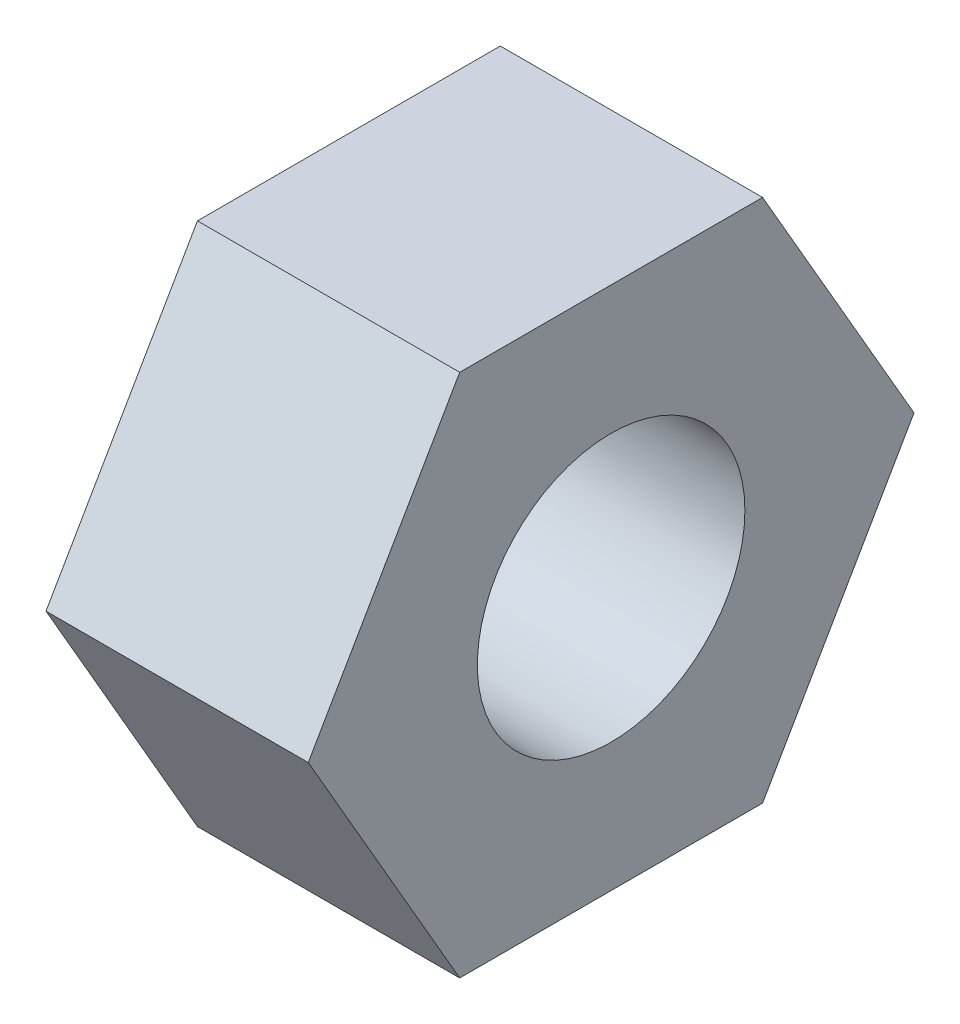
SolidWorks part; units mm, degrees
ref_plane "前视基准面" through (0, 0, 0) normal (0, 0, 1) x (1, 0, 0)
ref_plane "上视基准面" through (0, 0, 0) normal (0, 1, 0) x (1, 0, 0)
ref_plane "右视基准面" through (0, 0, 0) normal (1, 0, 0) x (0, 0, -1)
other "Configuration Table"
ref_plane "P_01_HEX_M12" through (0, 0, 0) normal (1, 0, 0) x (0, 0, -1)
sketch "草图1" plane through (0, 0, 0) normal (1, 0, 0) x (0, 0, -1)
  line L1 (11.547, 0) -> (5.7735, 10)
  line L2 (5.7735, 10) -> (-5.7735, 10)
  line L3 (-5.7735, 10) -> (-11.547, 0)
  line L4 (-11.547, 0) -> (-5.7735, -10)
  line L5 (-5.7735, -10) -> (5.7735, -10)
  line L6 (5.7735, -10) -> (11.547, 0)
  circle A0 centre (0, 0) radius 10 construction
  circle A1 centre (0, 0) radius 5.1
extrude "01_HEX_M12" add sketch "草图1" along normal blind 10
